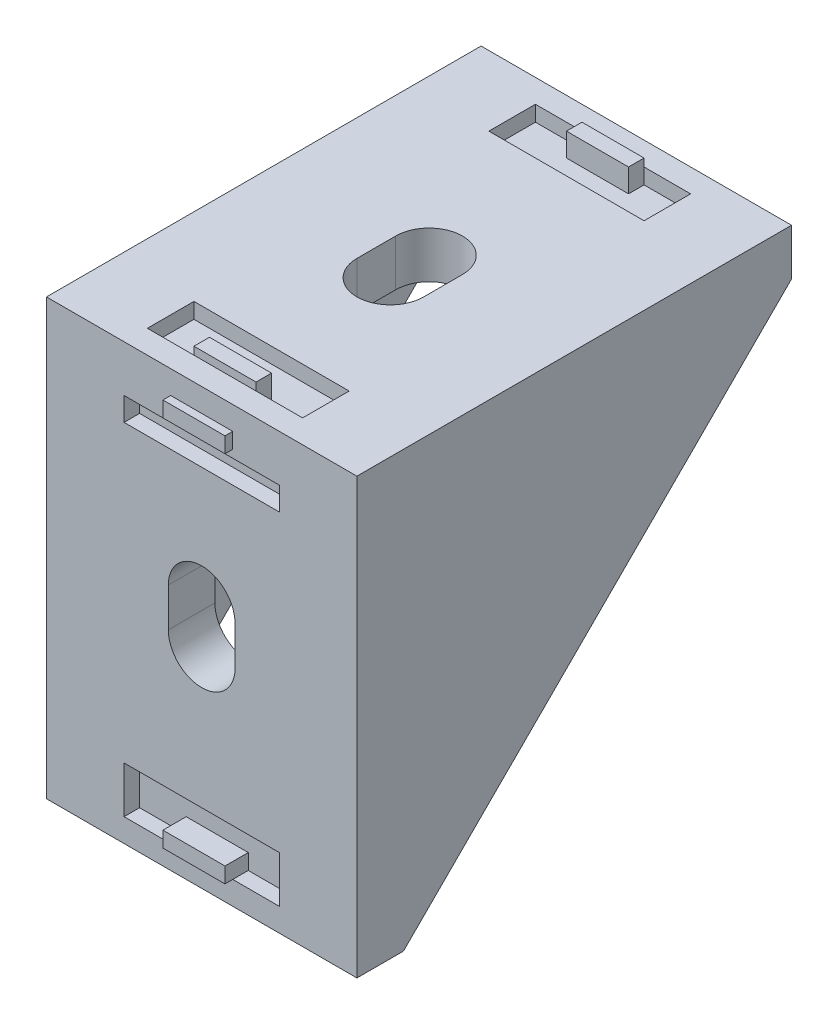
SolidWorks part; units mm, degrees
ref_plane "前视基准面" through (0, 0, 0) normal (0, 0, 1) x (1, 0, 0)
ref_plane "上视基准面" through (0, 0, 0) normal (0, 1, 0) x (1, 0, 0)
ref_plane "右视基准面" through (0, 0, 0) normal (1, 0, 0) x (0, 0, -1)
sketch "草图1" plane through (0, 0, 0) normal (0, 0, 1) x (1, 0, 0)
  line L0 (0, 0) -> (0, 48.2351) construction
  line L1 (0, 0) -> (65.177, 0) construction
  line L2 (-10, 31.4803) -> (10, 31.4803)
  line L3 (10, 31.4803) -> (10, 3.4803)
  line L4 (10, 3.4803) -> (-10, 3.4803)
  line L5 (2.15, 19.3303) -> (2.15, 16.8303)
  line L6 (-2.15, 19.3303) -> (-2.15, 16.8303)
  line L7 (-10, 31.4803) -> (-10, 3.4803)
  arc A0 (2.15, 19.3303) -> (-2.15, 19.3303) centre (0, 19.3303) ccw
  arc A1 (-2.15, 16.8303) -> (2.15, 16.8303) centre (0, 16.8303) ccw
  point P15 (0, 3.4803)
  point P16 (0, 31.4803)
  dimension "D1" = 4.3
  dimension "D2" = 4.3
  dimension "D3" = 28
  dimension "D4" = 10
  dimension "D5" = 2.5
  dimension "D6" = 12.15
extrude "凸台-拉伸1" add sketch "草图1" along normal blind 3
sketch "草图2" plane through (0, 0, 3) normal (0, 0, 1) x (1, 0, 0)
  line L0 (0, 21.5803) -> (0, 36.1122) construction
  line L1 (0, 21.5803) -> (17.262, 21.5803) construction
  line L2 (10, 31.4803) -> (-10, 31.4803) construction
  line L3 (-5, 29.9803) -> (5, 29.9803)
  line L4 (-5, 29.9803) -> (-5, 26.9803)
  line L5 (-5, 26.9803) -> (5, 26.9803)
  line L6 (5, 29.9803) -> (5, 26.9803)
  line L7 (-5, 29.9803) -> (5, 26.9803) construction
  line L8 (-5, 26.9803) -> (5, 29.9803) construction
  point P0 (0, 28.4803)
  dimension "D1" = 3
  dimension "D2" = 10
  dimension "D3" = 3
extrude "切除-拉伸1" cut sketch "草图2" against normal blind 1
sketch "草图3" plane through (0, 0, 2) normal (0, 0, 1) x (1, 0, 0)
  line L0 (0, 19.3303) -> (0, 33.3553) construction
  line L1 (-2, 28.9803) -> (-2, 29.9803)
  line L2 (5, 29.9803) -> (-5, 29.9803) construction
  line L3 (-2, 29.9803) -> (2, 29.9803)
  line L4 (2, 29.9803) -> (2, 28.9803)
  line L5 (2, 28.9803) -> (-2, 28.9803)
  dimension "D1" = 4
  dimension "D2" = 2
  dimension "D3" = 1
extrude "凸台-拉伸2" add sketch "草图3" along normal blind 1.5
ref_plane "基准面1" through (0, 17.4803, 0) normal (0, 1, 0) x (1, 0, 0)
mirror "镜向1" about plane through (0, 17.4803, 0) normal (0, 1, 0) of "凸台-拉伸2", "切除-拉伸1"
ref_plane "基准面3" through (0, 14.2401, -14.2401) normal (0, -0.7071, 0.7071) x (1, 0, 0)
mirror "镜向2" about plane through (0, 14.2401, -14.2401) normal (0, -0.7071, 0.7071) of "镜向1", "凸台-拉伸2", "切除-拉伸1", "凸台-拉伸1"
sketch "草图4" plane through (10, 0, 0) normal (1, 0, 0) x (0, 0, -1)
  line L0 (0, 3.4803) -> (25, 28.4803)
rib "筋2" sketch "草图4" sketch "草图4" thickness 2 extrusion direction parallel to sketch draft on no parameters "D1"=2
ref_plane "基准面4" through (0, 0, 0) normal (-1, 0, 0) x (0, 0, 1)
mirror "镜向3" about plane through (0, 0, 0) normal (-1, 0, 0) of "筋2"
